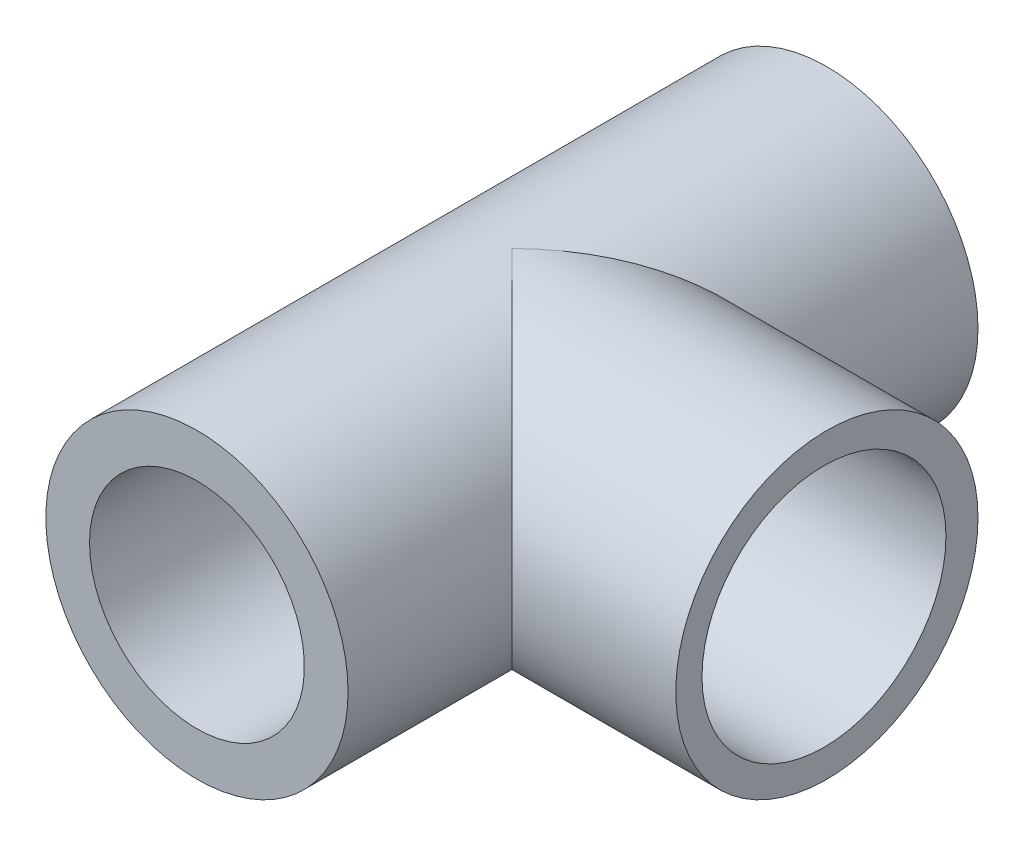
SolidWorks part; units mm, degrees
ref_plane "Front Plane" through (0, 0, 0) normal (0, 0, 1) x (1, 0, 0)
ref_plane "Top Plane" through (0, 0, 0) normal (0, 1, 0) x (1, 0, 0)
ref_plane "Right Plane" through (0, 0, 0) normal (1, 0, 0) x (0, 0, -1)
sketch "Sketch1" plane through (0, 0, 0) normal (0, 0, 1) x (1, 0, 0)
  circle A0 centre (0, 0) radius 16.4703
extrude "Boss-Extrude1" add sketch "Sketch1" along normal blind 68.6594
sketch "Sketch2" plane through (0, 0, 0) normal (1, 0, 0) x (0, 0, -1)
  line L0 (0, -16.4703) -> (0, 16.4703) construction
  circle A0 centre (-34.3297, 0) radius 16.4703
  dimension "D1" = 34.3297
extrude "Boss-Extrude2" add sketch "Sketch2" along normal blind 34.3297
sketch "Sketch3" plane through (34.3297, 0, 0) normal (1, 0, 0) x (0, 0, -1)
  circle A0 centre (-34.3297, 0) radius 11.7078
extrude "Cut-Extrude1" cut sketch "Sketch3" against normal blind 34.3297
sketch "Sketch4" plane through (34.3297, 0, 0) normal (1, 0, 0) x (0, 0, -1)
  circle A0 centre (-34.647, 0) radius 13.2953
extrude "Cut-Extrude2" cut sketch "Sketch4" against normal blind 25.7969
sketch "Sketch5" plane through (0, 0, 0) normal (0, 0, -1) x (-1, 0, 0)
  circle A0 centre (0, 0) radius 11.7078
extrude "Cut-Extrude3" cut sketch "Sketch5" against normal through all
